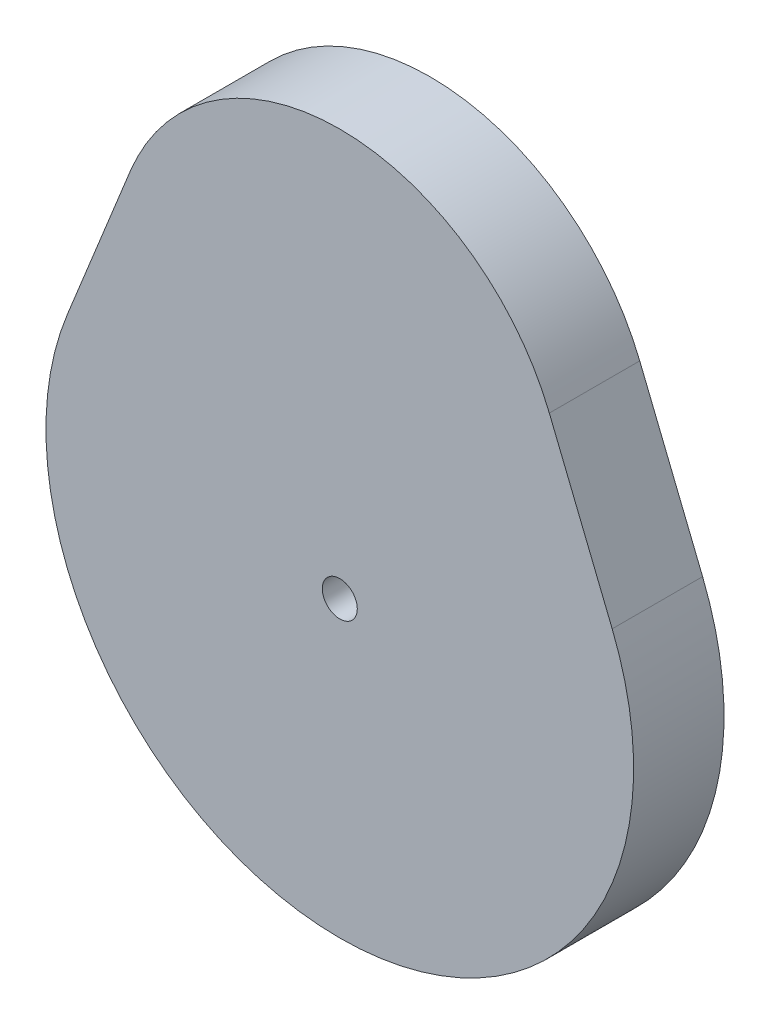
SolidWorks part; units mm, degrees
ref_plane "Front Plane" through (0, 0, 0) normal (0, 0, 1) x (1, 0, 0)
ref_plane "Top Plane" through (0, 0, 0) normal (0, 1, 0) x (1, 0, 0)
ref_plane "Right Plane" through (0, 0, 0) normal (1, 0, 0) x (0, 0, -1)
sketch "Sketch1" plane through (0, 0, 0) normal (0, 0, 1) x (1, 0, 0)
  line L0 (0, 25.4) -> (0, 0) construction
  line L1 (-29.433, 37.3062) -> (-38.2629, 15.4781)
  line L2 (29.433, 37.3063) -> (38.2629, 15.4781)
  circle A0 centre (0, 0) radius 41.275
  circle A1 centre (0, 25.4) radius 31.75
  dimension "D1" = 63.5
  dimension "D2" = 82.55
  dimension "D3" = 25.4
extrude "Boss-Extrude1" add sketch "Sketch1" along normal blind 12.7
hole_wizard "#10 (0.1935) Diameter Hole1" positions "Sketch3" profile "Sketch4" hole size "#10" standard "ANSI Inch" end condition through all
sketch "Sketch3" plane through (0, 0, 12.7) normal (0, 0, 1) x (1, 0, 0)
  point P0 (0, 0)
sketch "Sketch4" plane through (0, 0, 12.7) normal (1, 0, 0) x (0, -1, 0)
  line L0 (0, 0) -> (0, 12.7)
  line L1 (0, 12.7) -> (2.4574, 12.7)
  line L2 (2.4574, 12.7) -> (2.4574, 0)
  line L5 (2.4574, 0) -> (0, 0)
  line L11 (0, -6.35) -> (0, 107.95) construction
  dimension "Thru Hole Dia." = 4.9149
  dimension "Thru Hole Depth" = 12.7
